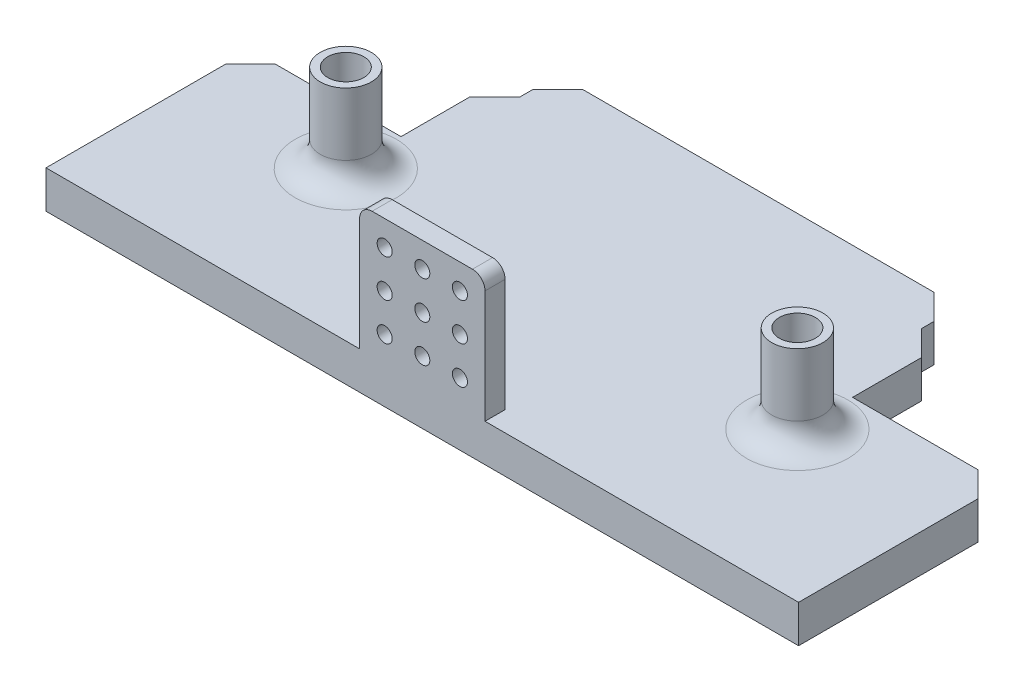
SolidWorks part; units mm, degrees
ref_plane "Front Plane" through (0, 0, 0) normal (0, 0, 1) x (1, 0, 0)
ref_plane "Top Plane" through (0, 0, 0) normal (0, 1, 0) x (1, 0, 0)
ref_plane "Right Plane" through (0, 0, 0) normal (1, 0, 0) x (0, 0, -1)
sketch "Sketch1" plane through (0, 0, 0) normal (0, 1, 0) x (1, 0, 0)
  line L1 (-75, 29.755) -> (75, 29.755)
  line L2 (-75, 29.755) -> (-75, -29.755)
  line L3 (-75, -29.755) -> (75, -29.755)
  line L4 (75, 29.755) -> (75, -29.755)
  line L5 (-75, 29.755) -> (75, -29.755) construction
  line L6 (-75, -29.755) -> (75, 29.755) construction
  point P0 (0, 0)
  dimension "D1" = 59.51
  dimension "D2" = 150
extrude "Boss-Extrude1" add sketch "Sketch1" along normal blind 7.5
sketch "Sketch2" plane through (0, 7.5, 0) normal (0, 1, 0) x (1, 0, 0)
  line L0 (-75, 0) -> (75, 0) construction
  line L1 (-75, 29.755) -> (-75, -29.755) construction
  line L2 (75, -29.755) -> (75, 29.755) construction
  circle A0 centre (-45, 0) radius 5.1
  circle A1 centre (45, 0) radius 5.1
  dimension "D1" = 30
  dimension "D2" = 30
extrude "Boss-Extrude2" add sketch "Sketch2" along normal blind 17.5
fillet "Fillet1" radius 5 2 edges at (45, 7.5, 5.1) (-45, 7.5, 5.1)
sketch "Sketch3" plane through (0, 25, 0) normal (0, 1, 0) x (1, 0, 0)
  circle A0 centre (-45, 0) radius 3.6
  circle A1 centre (45, 0) radius 3.6
extrude "Cut-Extrude1" cut sketch "Sketch3" against normal blind 25
sketch "Sketch4" plane through (0, 0, -29.755) normal (0, 0, -1) x (-1, 0, 0)
  line L0 (-75, 0) -> (75, 0) construction
  line L1 (-75, 7.5) -> (-45, 7.5)
  line L2 (-75, 7.5) -> (-75, 0)
  line L3 (-75, 0) -> (-45, 0)
  line L4 (-45, 7.5) -> (-45, 0)
  line L6 (75, 7.5) -> (45, 7.5)
  line L7 (75, 7.5) -> (75, 0)
  line L8 (75, 0) -> (45, 0)
  line L9 (45, 7.5) -> (45, 0)
  dimension "D1" = 30
  dimension "D2" = 30
extrude "Cut-Extrude2" cut sketch "Sketch4" against normal blind 18.75
chamfer "Chamfer1" distance 5 angle 45 4 edges at (75, 3.75, -11.005) (45, 3.75, -29.755) (-45, 3.75, -29.755) (-75, 3.75, -11.005)
sketch "Sketch5" plane through (0, 0, -29.755) normal (0, 0, -1) x (-1, 0, 0)
  line L1 (-40, 7.5) -> (40, 7.5)
  line L2 (-40, 7.5) -> (-40, 0)
  line L3 (-40, 0) -> (40, 0)
  line L4 (40, 7.5) -> (40, 0)
extrude "Boss-Extrude3" add sketch "Sketch5" along normal blind 7.5
chamfer "Chamfer2" distance 5 angle 45 2 edges at (40, 3.75, -37.255) (-40, 3.75, -37.255)
sketch "Sketch6" plane through (0, 0, -37.255) normal (0, 0, -1) x (-1, 0, 0)
  line L0 (-35, 3.75) -> (35, 3.75) construction
  line L1 (-35, 7.5) -> (-35, 0) construction
  line L2 (35, 0) -> (35, 7.5) construction
  circle A0 centre (-15, 3.75) radius 1.5
  circle A1 centre (15, 3.75) radius 1.5
  point P10 (0, 3.75)
  dimension "D1" = 15
  dimension "D2" = 15
extrude "Cut-Extrude3" cut sketch "Sketch6" against normal blind 7.5
sketch "Sketch7" plane through (0, 7.5, 0) normal (0, 1, 0) x (1, 0, 0)
  line L0 (0, -29.755) -> (0, 37.255) construction
  line L1 (-75, -29.755) -> (75, -29.755) construction
  line L2 (-35, 37.255) -> (35, 37.255) construction
  line L3 (-43.2004, -24.755) -> (-25.6652, -24.755) construction
  line L4 (-12.5, -25.755) -> (-12.5, -29.755) construction
  line L5 (12.5, -25.755) -> (12.5, -29.755) construction
  line L7 (-12.5, -25.755) -> (12.5, -25.755)
  line L8 (-12.5, -25.755) -> (-12.5, -29.755)
  line L9 (-12.5, -29.755) -> (12.5, -29.755)
  line L10 (12.5, -25.755) -> (12.5, -29.755)
  dimension "D1" = 5
  dimension "D2" = 12.5
  dimension "D3" = 12.5
  dimension "D4" = 4
extrude "Boss-Extrude4" add sketch "Sketch7" along normal blind 25
sketch "Sketch8" plane through (0, 0, 25.755) normal (0, 0, -1) x (-1, 0, 0)
  line L0 (-12.5, 31.25) -> (12.5, 31.25) construction
  line L1 (-12.5, 32.5) -> (-12.5, 7.5) construction
  line L2 (12.5, 32.5) -> (12.5, 7.5) construction
  line L3 (-12.5, 32.5) -> (12.5, 32.5) construction
  line L4 (-12.5, 8.75) -> (12.5, 8.75) construction
  line L5 (-11.25, 32.5) -> (-11.25, 8.75) construction
  line L6 (11.25, 32.5) -> (11.25, 8.75) construction
  line L7 (0, 31.25) -> (0, 8.75) construction
  line L8 (-3.75, 31.25) -> (-3.75, 8.75) construction
  line L9 (3.75, 31.25) -> (3.75, 8.75) construction
  line L10 (-11.25, 23.75) -> (11.25, 23.75) construction
  line L11 (-11.25, 16.25) -> (11.25, 16.25) construction
  line L12 (-7.5, 31.25) -> (-7.5, 8.75) construction
  line L13 (7.5, 31.25) -> (7.5, 8.75) construction
  line L14 (-11.25, 27.5) -> (11.25, 27.5) construction
  line L15 (-11.25, 12.5) -> (11.25, 12.5) construction
  circle A0 centre (-7.5, 20) radius 1.5
  circle A1 centre (0, 20) radius 1.5
  circle A2 centre (-7.5, 27.5) radius 1.5
  circle A3 centre (0, 27.5) radius 1.5
  circle A4 centre (7.5, 27.5) radius 1.5
  circle A5 centre (7.5, 20) radius 1.5
  circle A6 centre (-7.5, 12.5) radius 1.5
  circle A7 centre (0, 12.5) radius 1.5
  circle A8 centre (7.5, 12.5) radius 1.5
  dimension "D10" = 3.75
  dimension "D12" = 3.75
  dimension "D1" = 1.25
  dimension "D2" = 1.25
  dimension "D3" = 1.25
  dimension "D4" = 1.25
  dimension "D5" = 3.75
  dimension "D6" = 3.75
  dimension "D7" = 7.5
  dimension "D8" = 7.5
  dimension "D9" = 3.75
  dimension "D11" = 3.75
extrude "Cut-Extrude4" cut sketch "Sketch8" against normal blind 5
fillet "Fillet2" radius 2.5 2 edges at (12.5, 32.5, 27.755) (-12.5, 32.5, 27.755)
